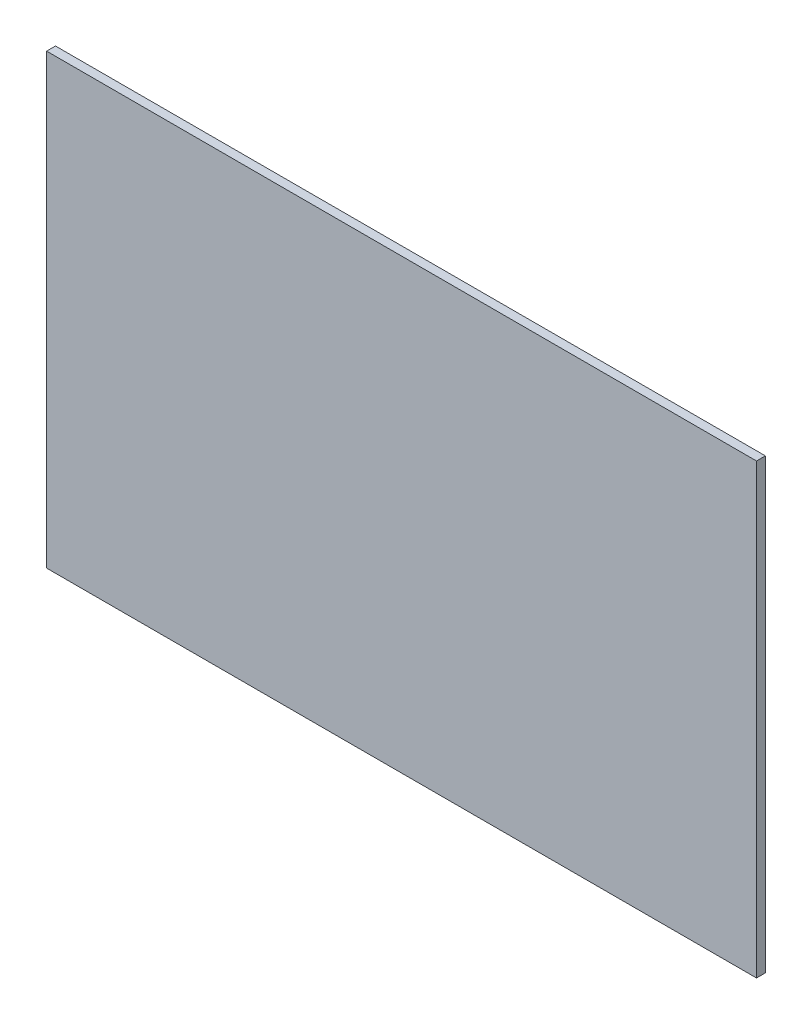
SolidWorks part; units mm, degrees
material "Oak"
ref_plane "Front" through (0, 0, 0) normal (0, 0, 1) x (1, 0, 0)
ref_plane "Top" through (0, 0, 0) normal (0, 1, 0) x (1, 0, 0)
ref_plane "Right" through (0, 0, 0) normal (1, 0, 0) x (0, 0, -1)
sketch "Sketch1" plane through (0, 0, 0) normal (0, 0, 1) x (1, 0, 0)
  line L0 (0, 480.95) -> (0, 0)
  line L1 (0, 0) -> (762.5, 0)
  line L2 (762.5, 0) -> (762.5, 480.95)
  line L3 (762.5, 480.95) -> (0, 480.95)
  dimension "D1" = 762.5
  dimension "D2" = 480.95
extrude "Boss-Extrude1" add sketch "Sketch1" along normal blind 9.525
